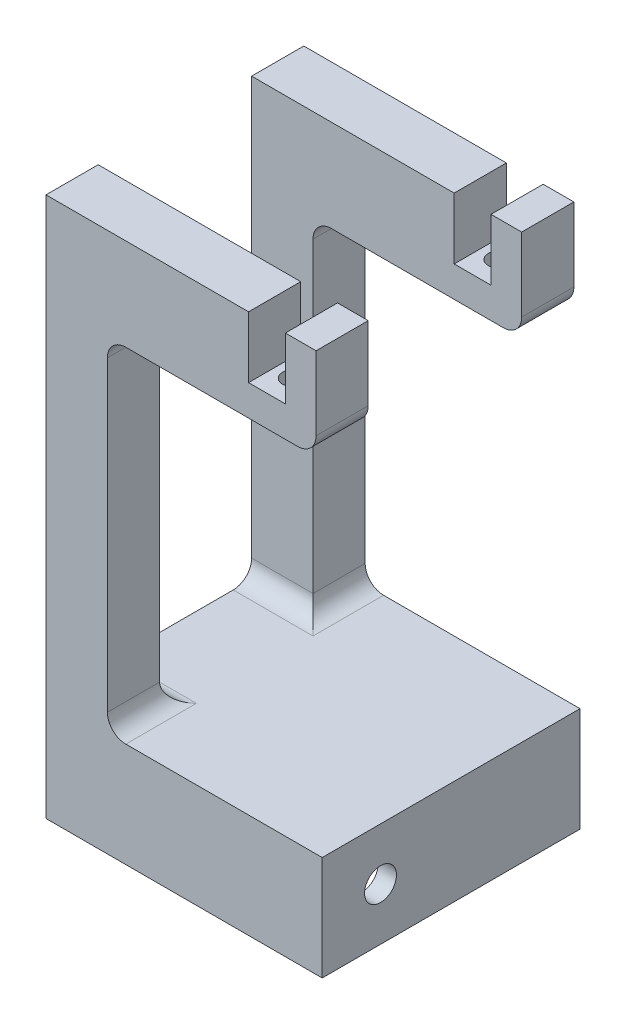
SolidWorks part; units mm, degrees
ref_plane "Front Plane" through (0, 0, 0) normal (0, 0, 1) x (1, 0, 0)
ref_plane "Top Plane" through (0, 0, 0) normal (0, 1, 0) x (1, 0, 0)
ref_plane "Right Plane" through (0, 0, 0) normal (1, 0, 0) x (0, 0, -1)
sketch "Sketch1" plane through (0, 0, 0) normal (0, 0, 1) x (1, 0, 0)
  line L0 (10, 17) -> (45, 17)
  line L1 (0, 0) -> (45, 0)
  line L2 (0, 0) -> (0, 88)
  line L3 (0, 88) -> (33, 88)
  line L5 (10, 17) -> (10, 73)
  line L6 (10, 73) -> (44, 73)
  line L8 (45, 17) -> (45, 0)
  line L19 (44, 88) -> (44, 73)
  line L20 (33, 88) -> (39, 88) construction
  line L21 (33, 88) -> (39, 88) construction
  line L22 (33, 88) -> (33, 78)
  line L23 (33, 78) -> (39, 78)
  line L24 (39, 88) -> (39, 78)
  line L25 (39, 88) -> (44, 88)
  dimension "D2" = 88
  dimension "D3" = 44
  dimension "D4" = 45
  dimension "D5" = 5
  dimension "D6" = 6
  dimension "D7" = 10
  dimension "D1" = 17
  dimension "D8" = 15
  dimension "D9" = 10
extrude "Boss-Extrude1" add sketch "Sketch1" along normal blind 42
sketch "Sketch2" plane through (0, 0, 0) normal (-1, 0, 0) x (0, 0, 1)
  line L0 (42, 88) -> (0, 88) construction
  line L1 (8.5, 88) -> (33.5, 88)
  line L2 (8.5, 88) -> (8.5, 17)
  line L3 (8.5, 17) -> (33.5, 17)
  line L4 (33.5, 88) -> (33.5, 17)
  line L5 (42, 0) -> (0, 0) construction
  point P9 (21, 0)
  point P10 (21, 17)
  dimension "D1" = 17
  dimension "D2" = 25
extrude "Cut-Extrude1" cut sketch "Sketch2" against normal through all
sketch "Sketch4" plane through (0, 78, 0) normal (0, 1, 0) x (1, 0, 0)
  line L0 (36, -33.5) -> (36, -42) construction
  line L1 (39, -33.5) -> (33, -33.5) construction
  line L2 (39, -42) -> (33, -42) construction
  line L3 (0, -21) -> (45, -21) construction
  line L4 (0, -8.5) -> (0, -33.5) construction
  line L5 (45, -42) -> (45, 0) construction
  circle A0 centre (36, -37.75) radius 1.7
  circle A1 centre (36, -4.25) radius 1.7
  dimension "D1" = 3.4
extrude "Cut-Extrude2" cut sketch "Sketch4" against normal up to next
sketch "Sketch7" plane through (45, 0, 0) normal (1, 0, 0) x (0, 0, -1)
  line L1 (-42, 0) -> (-42, 17) construction
  line L2 (-42, 17) -> (-33.5, 17) construction
  circle A0 centre (-32.5, 8.5) radius 2.6
  dimension "D1" = 5.2
  dimension "D2" = 9.5
  dimension "D3" = 8.5
extrude "Cut-Extrude3" cut sketch "Sketch7" against normal blind 10
fillet "Fillet1" radius 3 4 edges at (10, 17, 37.75) (5, 17, 33.5) (5, 17, 8.5) (10, 17, 4.25)
fillet "Fillet2" radius 3 4 edges at (44, 73, 4.25) (44, 73, 37.75) (10, 73, 37.75) (10, 73, 4.25)
sketch "Sketch8" plane through (0, 0, 0) normal (0, -1, 0) x (1, 0, 0)
  line L8 (3, 3) -> (42, 3)
  line L9 (42, 3) -> (42, 39)
  line L10 (42, 39) -> (3, 39)
  line L11 (3, 39) -> (3, 3)
  line L12 (3, 3) -> (42, 3)
  line L13 (42, 3) -> (42, 39)
  line L14 (42, 39) -> (3, 39)
  line L15 (3, 39) -> (3, 3)
  dimension "D1" = 3
extrude "Cut-Extrude4" cut sketch "Sketch8" against normal blind 14
